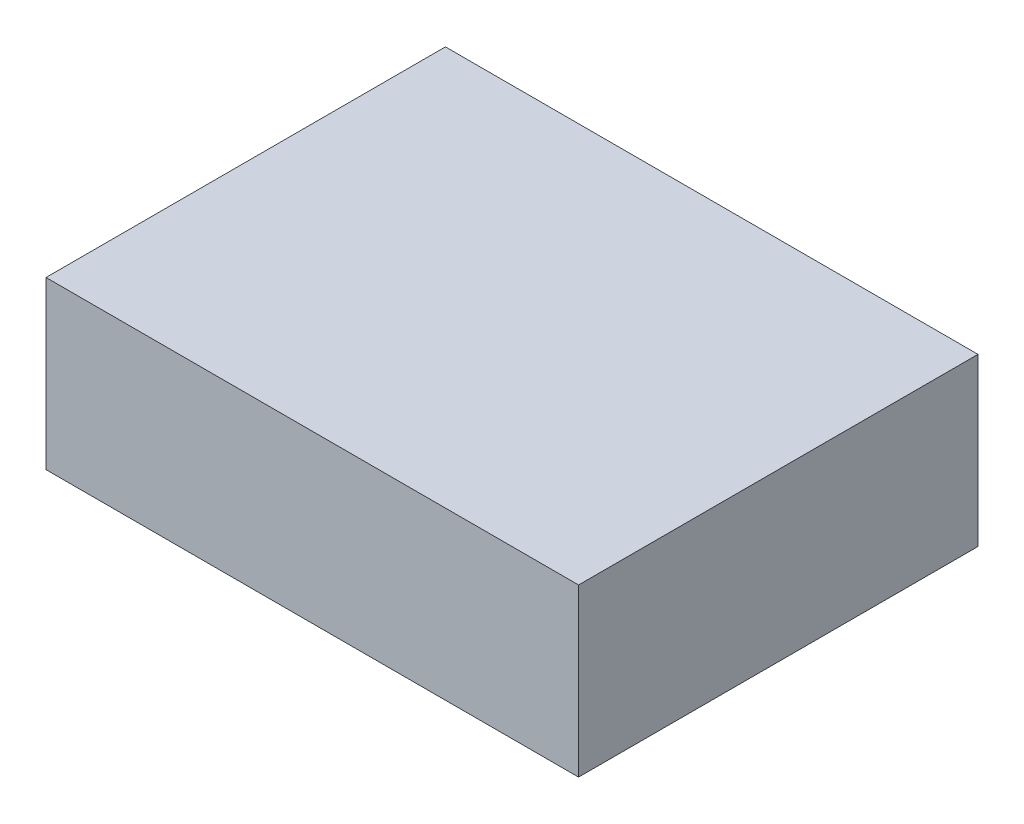
SolidWorks part; units mm, degrees
ref_plane "Front Plane" through (0, 0, 0) normal (0, 0, 1) x (1, 0, 0)
ref_plane "Top Plane" through (0, 0, 0) normal (0, 1, 0) x (1, 0, 0)
ref_plane "Right Plane" through (0, 0, 0) normal (1, 0, 0) x (0, 0, -1)
sketch "Sketch2" plane through (0, 0, 0) normal (0, 1, 0) x (1, 0, 0)
  line L1 (-160, 120) -> (160, 120)
  line L2 (-160, 120) -> (-160, -120)
  line L3 (-160, -120) -> (160, -120)
  line L4 (160, 120) -> (160, -120)
  line L5 (-160, 120) -> (160, -120) construction
  line L6 (-160, -120) -> (160, 120) construction
  point P0 (0, 0)
  dimension "D1" = 320
  dimension "D2" = 240
extrude "Boss-Extrude1" add sketch "Sketch2" along normal blind 100
